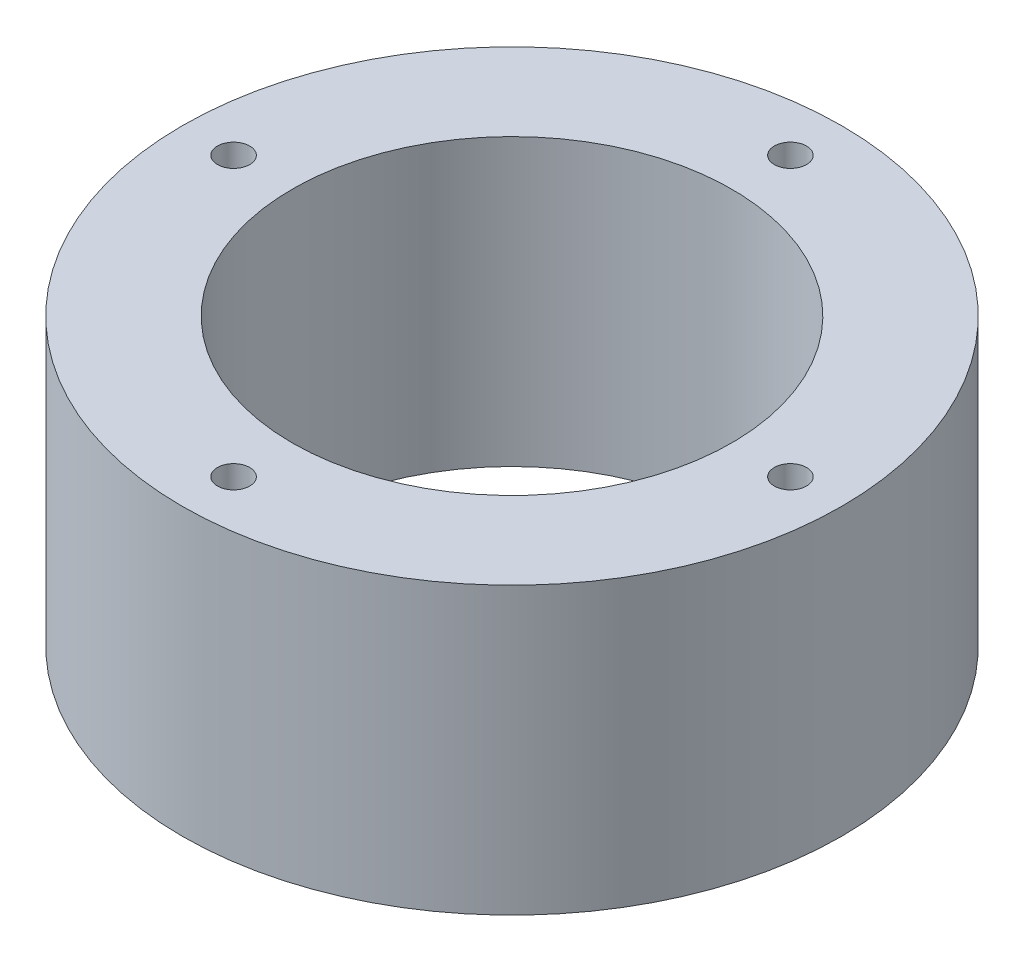
SolidWorks part; units mm, degrees
material "ABS"
ref_plane "前视基准面" through (0, 0, 0) normal (0, 0, 1) x (1, 0, 0)
ref_plane "上视基准面" through (0, 0, 0) normal (0, 1, 0) x (1, 0, 0)
ref_plane "右视基准面" through (0, 0, 0) normal (1, 0, 0) x (0, 0, -1)
other "Configuration Table"
sketch "草图1" plane through (0, 0, 0) normal (0, 1, 0) x (1, 0, 0)
  circle A0 centre (0, 0) radius 15
  circle A1 centre (0, 0) radius 19 construction
  circle A2 centre (0, 0) radius 22.5
  circle A3 centre (0, 19) radius 1.1
  circle A4 centre (19, 0) radius 1.1
  circle A5 centre (0, -19) radius 1.1
  circle A6 centre (-19, 0) radius 1.1
  point P15 (0, 0)
  dimension "D1" = 38
  dimension "D2" = 30
  dimension "D3" = 45
  dimension "D4" = 2.2
  dimension "D5" = 4
extrude "凸台-拉伸1" add sketch "草图1" along normal blind 19.5
